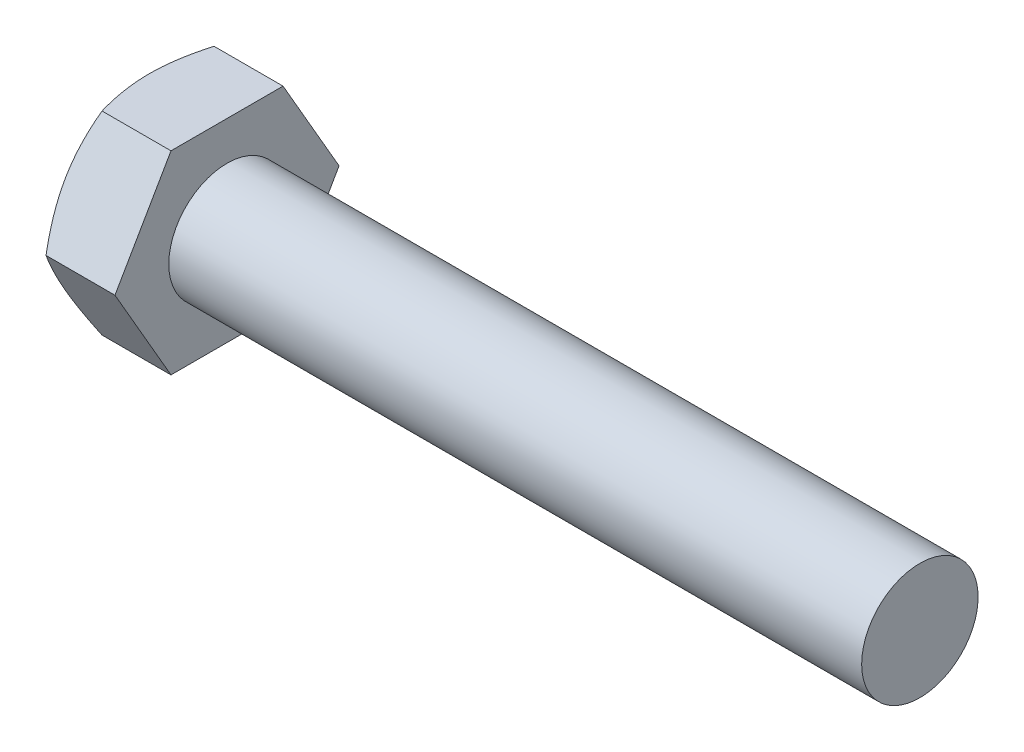
SolidWorks part; units mm, degrees
ref_plane "Front Plane" through (0, 0, 0) normal (0, 0, 1) x (1, 0, 0)
ref_plane "Top Plane" through (0, 0, 0) normal (0, 1, 0) x (1, 0, 0)
ref_plane "Right Plane" through (0, 0, 0) normal (1, 0, 0) x (0, 0, -1)
sketch "Sketch2" plane through (0, 0, 0) normal (1, 0, 0) x (0, 0, -1)
  circle A0 centre (0, 0) radius 3
  dimension "D1" = 6
extrude "Boss-Extrude1" add sketch "Sketch2" along normal blind 35.7
cosmetic thread "Cosmetic Thread1" parameters "D1"=6, "D2"=4.891
sketch "Sketch3" plane through (0, 0, 0) normal (-1, 0, 0) x (0, 0, 1)
  line L1 (5.7735, 0) -> (2.8868, 5)
  line L2 (2.8868, 5) -> (-2.8868, 5)
  line L3 (-2.8868, 5) -> (-5.7735, 0)
  line L4 (-5.7735, 0) -> (-2.8868, -5)
  line L5 (-2.8868, -5) -> (2.8868, -5)
  line L6 (2.8868, -5) -> (5.7735, 0)
  circle A0 centre (0, 0) radius 5 construction
  dimension "D1" = 10
extrude "Boss-Extrude2" add sketch "Sketch3" along normal blind 4
sketch "Sketch5" plane through (0, 0, 0) normal (0, 1, 0) x (1, 0, 0)
  line L0 (-4, 5) -> (-4, -5) construction
  line L1 (-4, -2.8868) -> (-4, 2.8868) construction
  line L2 (-4, 5) -> (-4, 5.7735)
  line L3 (-4, 5.7735) -> (-3.5534, 5.7735)
  line L4 (-4, 5.7735) -> (0, 5.7735) construction
  line L5 (-3.5534, 5.7735) -> (-4, 5)
  dimension "D1" = 10
  dimension "D2" = 5
  dimension "D3" = 30
revolve "Cut-Revolve1" cut sketch "Sketch5" angle 360 about axis through (35.7, 0, 0) along (-1, 0, 0)
